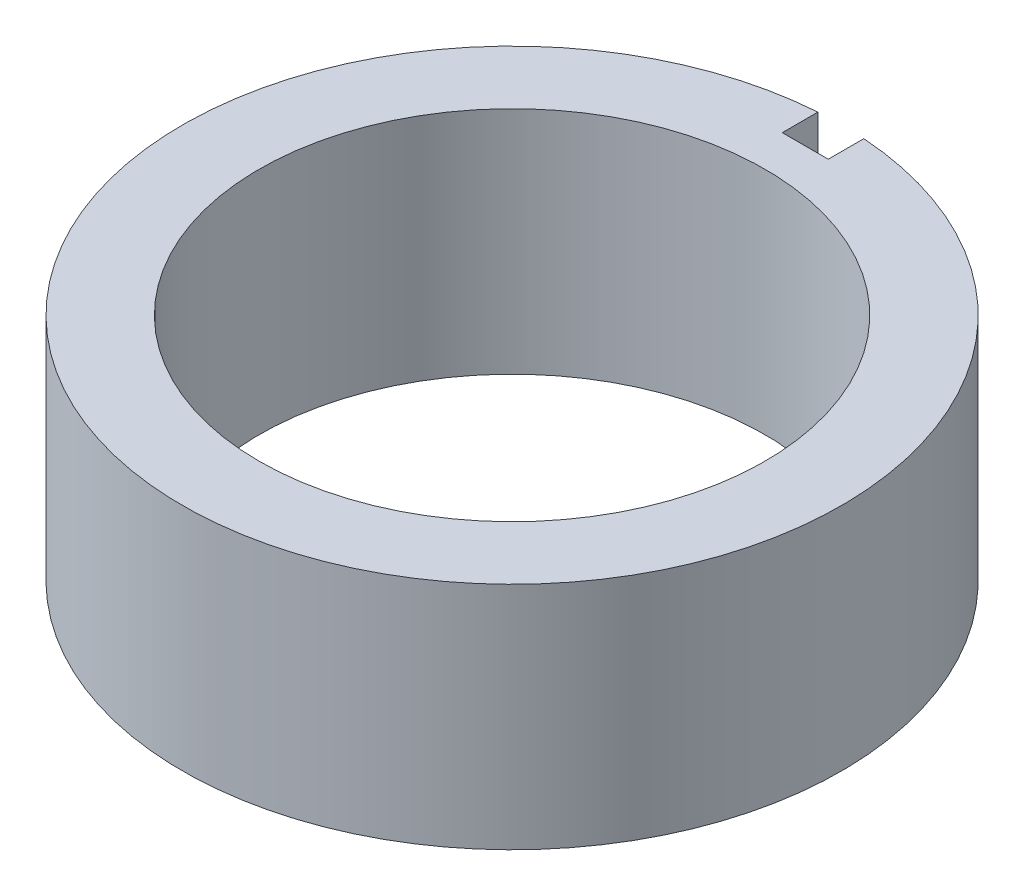
SolidWorks part; units mm, degrees
ref_plane "Front Plane" through (0, 0, 0) normal (0, 0, 1) x (1, 0, 0)
ref_plane "Top Plane" through (0, 0, 0) normal (0, 1, 0) x (1, 0, 0)
ref_plane "Right Plane" through (0, 0, 0) normal (1, 0, 0) x (0, 0, -1)
sketch "Sketch1" plane through (0, 0, 0) normal (0, 1, 0) x (1, 0, 0)
  line L0 (-3, 42.8952) -> (-3, 38.2517)
  line L1 (3, 42.8952) -> (3, 38.2517)
  line L2 (-3, 38.2517) -> (3, 38.2517)
  circle A0 centre (0, 0) radius 33
  arc A1 (-3, 42.8952) -> (3, 42.8952) centre (0, 0) ccw
  circle A2 centre (0, 0) radius 43 construction
  dimension "D1" = 10
  dimension "D2" = 3
  dimension "D3" = 3
extrude "Boss-Extrude1" add sketch "Sketch1" along normal blind 30
ref_plane "Plane1" through (0, 15, 0) normal (0, 1, 0) x (1, 0, 0)
